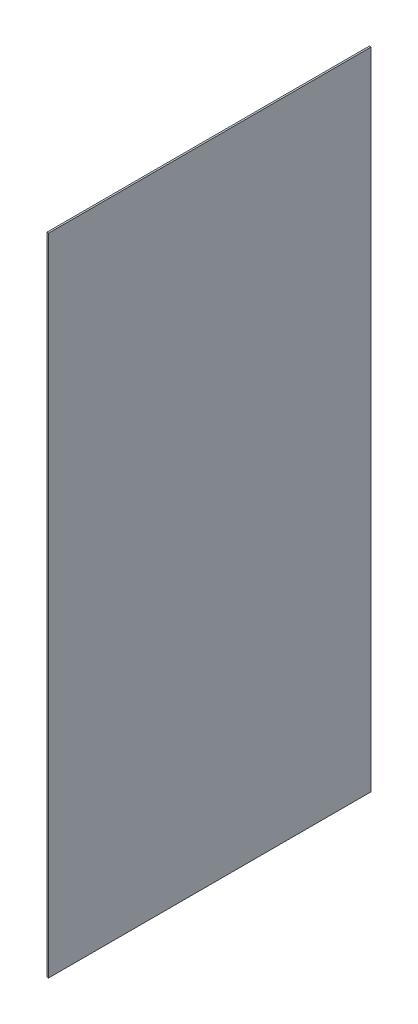
SolidWorks part; units mm, degrees
ref_plane "Front Plane" through (0, 0, 0) normal (0, 0, 1) x (1, 0, 0)
ref_plane "Top Plane" through (0, 0, 0) normal (0, 1, 0) x (1, 0, 0)
ref_plane "Right Plane" through (0, 0, 0) normal (1, 0, 0) x (0, 0, -1)
sketch "Sketch1" plane through (0, 0, 0) normal (1, 0, 0) x (0, 0, -1)
  line L1 (304.8, -609.6) -> (-304.8, -609.6)
  line L2 (304.8, -609.6) -> (304.8, 609.6)
  line L3 (304.8, 609.6) -> (-304.8, 609.6)
  line L4 (-304.8, -609.6) -> (-304.8, 609.6)
  line L5 (304.8, -609.6) -> (-304.8, 609.6) construction
  line L6 (304.8, 609.6) -> (-304.8, -609.6) construction
  point P0 (0, 0)
  dimension "D1" = 609.6
  dimension "D2" = 1219.2
extrude "Boss-Extrude1" add sketch "Sketch1" along normal blind 3.175
